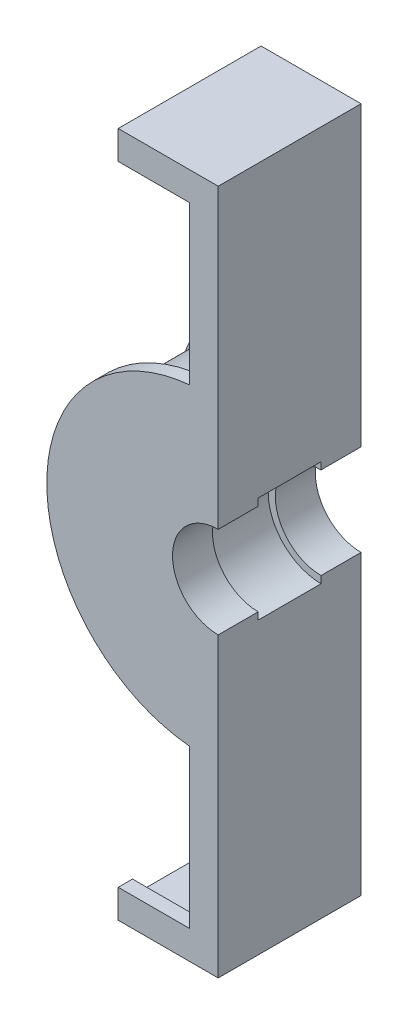
SolidWorks part; units mm, degrees
ref_plane "Alzado" through (0, 0, 0) normal (0, 0, 1) x (1, 0, 0)
ref_plane "Planta" through (0, 0, 0) normal (0, 1, 0) x (1, 0, 0)
ref_plane "Vista lateral" through (0, 0, 0) normal (1, 0, 0) x (0, 0, -1)
sketch "Croquis1" plane through (0, 0, 0) normal (0, 0, 1) x (1, 0, 0)
  line L18 (0, 50) -> (0, 115)
  line L19 (0, 115) -> (-30, 115)
  line L20 (-30, 115) -> (-30, 120)
  line L21 (-30, 120) -> (5, 120)
  line L22 (5, 120) -> (5, 45)
  line L23 (5, -120) -> (-30, -120)
  line L24 (-30, -120) -> (-30, -115)
  line L25 (-30, -115) -> (0, -115)
  line L26 (0, -50) -> (0, -115)
  line L27 (0, 45) -> (5, 45)
  line L28 (0, -45) -> (5, -45)
  line L29 (5, -45) -> (5, -120)
  arc A6 (0, 50) -> (0, -50) centre (0, 0) ccw
  arc A7 (0, 45) -> (0, -45) centre (0, 0) ccw
  point P0 (0, 0)
extrude "Saliente-Extruir1" add sketch "Croquis1" along normal blind 40
sketch "Croquis2" plane through (0, 0, 40) normal (0, 0, 1) x (1, 0, 0)
  line L0 (5, 120) -> (-30, 120)
  line L1 (-30, 120) -> (-30, 110)
  line L2 (-30, 110) -> (-5, 110)
  line L3 (-5, 110) -> (-5, 54.7723)
  line L4 (5, 120) -> (5, 45)
  line L5 (5, -120) -> (5, -45) construction
  line L6 (5, -120) -> (-30, -120)
  line L7 (-30, -120) -> (-30, -110)
  line L8 (-30, -110) -> (-5, -110)
  line L9 (-5, -110) -> (-5, -54.7723)
  line L10 (0, 45) -> (5, 45)
  line L11 (0, -45) -> (5, -45)
  line L12 (5, -45) -> (5, -120)
  arc A1 (-5, 54.7723) -> (-5, -54.7723) centre (0, 0) ccw
  arc A2 (0, 45) -> (0, -45) centre (0, 0) ccw
extrude "Saliente-Extruir2" add sketch "Croquis2" along normal blind 5
ref_plane "Plano1" through (0, 0, 20) normal (0, 0, 1) x (1, 0, 0)
mirror "Simetría1" about plane through (0, 0, 20) normal (0, 0, 1) of "Saliente-Extruir2"
sketch "Croquis3" plane through (0, 0, -5) normal (0, 0, -1) x (-1, 0, 0)
  line L0 (-5, 45.1118) -> (-5, 18.5)
  line L1 (-5, -18.5) -> (-5, -44.7214)
  line L2 (-5, 45.1118) -> (0, 45)
  line L4 (-5, -44.7214) -> (-5, -45)
  line L5 (-5, -45) -> (0, -45)
  arc A0 (-5, -18.5) -> (-5, 18.5) centre (-5, 0) ccw
  arc A1 (0, -45) -> (0, 45) centre (0, 0) ccw
extrude "Saliente-Extruir3" add sketch "Croquis3" against normal blind 50
sketch "Croquis4" plane through (0, 0, -5) normal (0, 0, -1) x (-1, 0, 0)
  line L0 (-5, 18.5) -> (-5, 16)
  line L1 (-5, -18.5) -> (-5, -16)
  arc A0 (-5, -18.5) -> (-5, 18.5) centre (-5, 0) ccw
  arc A1 (-5, -16) -> (-5, 16) centre (-5, 0) ccw
extrude "Saliente-Extruir4" add sketch "Croquis4" against normal blind 14
mirror "Simetría2" about plane through (0, 0, 20) normal (0, 0, 1) of "Saliente-Extruir4"
